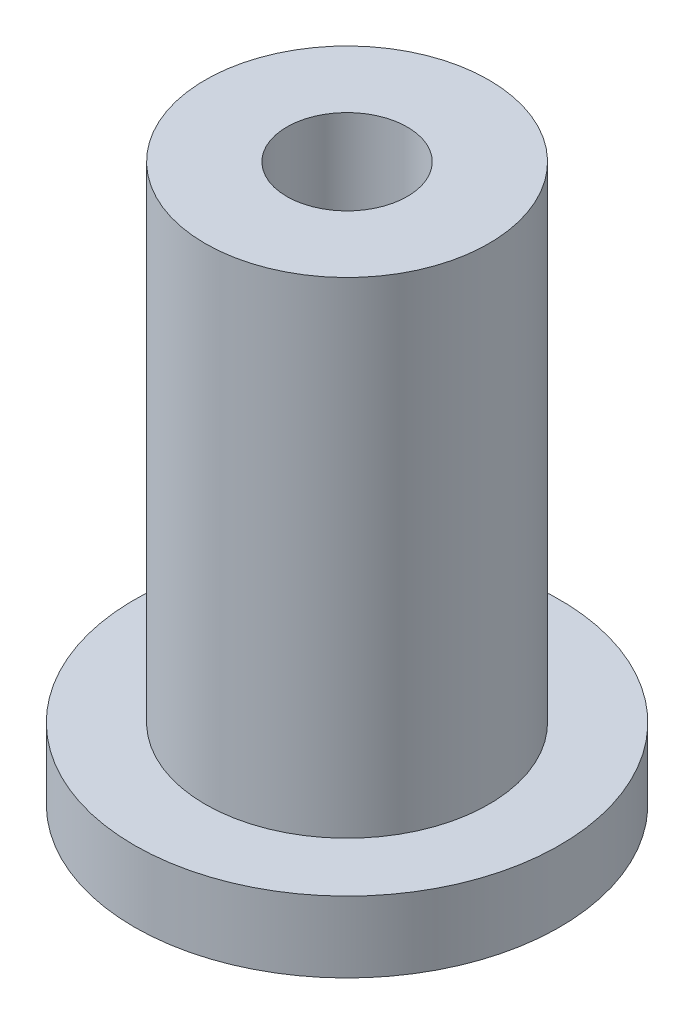
SolidWorks part; units mm, degrees
ref_plane "Front Plane" through (0, 0, 0) normal (0, 0, 1) x (1, 0, 0)
ref_plane "Top Plane" through (0, 0, 0) normal (0, 1, 0) x (1, 0, 0)
ref_plane "Right Plane" through (0, 0, 0) normal (1, 0, 0) x (0, 0, -1)
ref_plane "Plane1" through (0, -29.3, 0) normal (0, 1, 0) x (1, 0, 0)
sketch "Sketch1" plane through (0, -29.3, 0) normal (0, 1, 0) x (1, 0, 0)
  circle A0 centre (137.2, -306.23) radius 6
extrude "Boss-Extrude1" add sketch "Sketch1" along normal blind 2
sketch "Sketch2" plane through (0, -29.3, 0) normal (0, 1, 0) x (1, 0, 0)
  circle A0 centre (137.2, -306.23) radius 4
extrude "Boss-Extrude2" add sketch "Sketch2" along normal blind 15.7
sketch "Sketch3" plane through (0, -29.3, 0) normal (0, 1, 0) x (1, 0, 0)
  circle A0 centre (137.2, -306.23) radius 1.7
extrude "Cut-Extrude1" cut sketch "Sketch3" along normal through all
